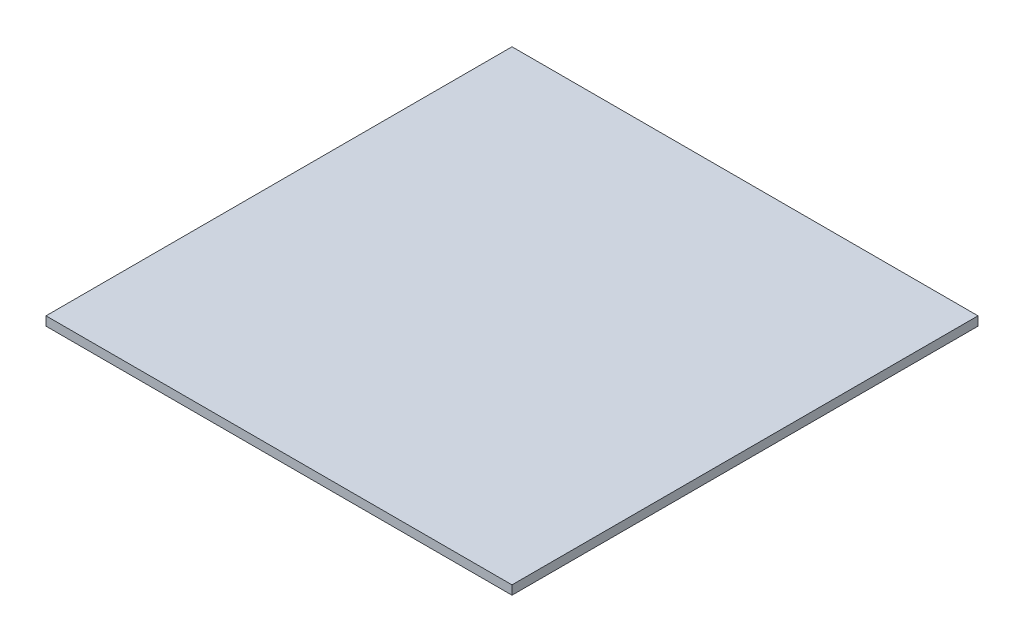
SolidWorks part; units mm, degrees
ref_plane "Front Plane" through (0, 0, 0) normal (0, 0, 1) x (1, 0, 0)
ref_plane "Top Plane" through (0, 0, 0) normal (0, 1, 0) x (1, 0, 0)
ref_plane "Right Plane" through (0, 0, 0) normal (1, 0, 0) x (0, 0, -1)
sketch "Sketch1" plane through (0, 0, 0) normal (0, 1, 0) x (1, 0, 0)
  line L1 (0, 0) -> (220, 0)
  line L2 (0, 0) -> (0, 220)
  line L3 (0, 220) -> (220, 220)
  line L4 (220, 0) -> (220, 220)
  dimension "D1" = 220
  dimension "D2" = 220
extrude "Boss-Extrude1" add sketch "Sketch1" along normal blind 4.25
